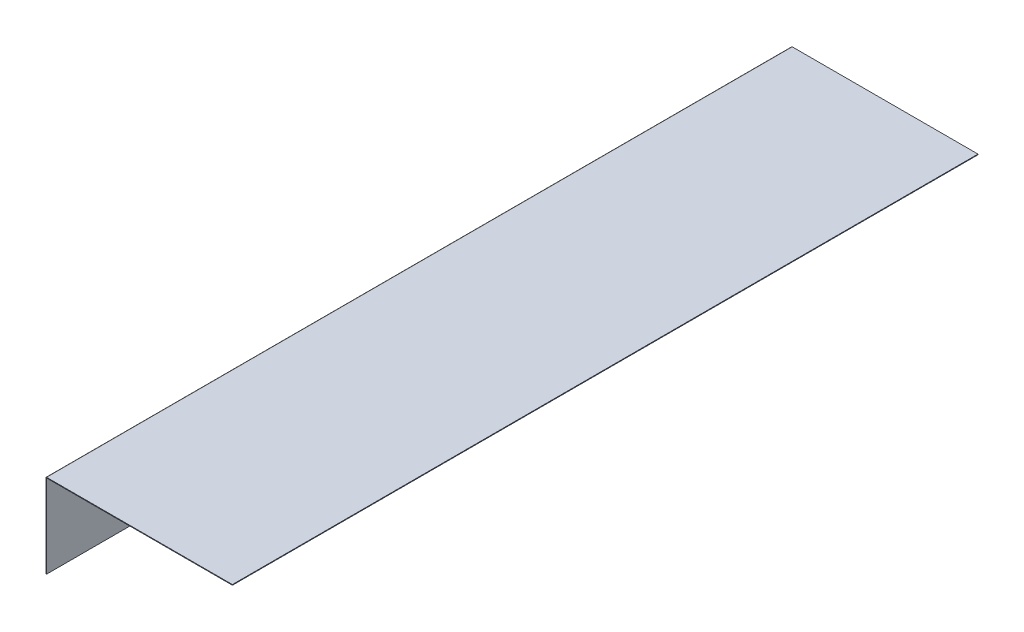
SolidWorks part; units mm, degrees
ref_plane "Front Plane" through (0, 0, 0) normal (0, 0, 1) x (1, 0, 0)
ref_plane "Top Plane" through (0, 0, 0) normal (0, 1, 0) x (1, 0, 0)
ref_plane "Right Plane" through (0, 0, 0) normal (1, 0, 0) x (0, 0, -1)
sketch "Sketch1" plane through (0, 0, 0) normal (0, 0, 1) x (1, 0, 0)
  line L0 (0, 0) -> (0, 135)
  line L1 (0, 135) -> (300, 135)
  line L2 (300, 135) -> (300, 134)
  line L3 (300, 134) -> (1, 134)
  line L4 (1, 134) -> (1, 0)
  line L5 (1, 0) -> (0, 0)
  dimension "D1" = 1
  dimension "D2" = 1
  dimension "D3" = 300
  dimension "D4" = 135
extrude "Boss-Extrude1" add sketch "Sketch1" along normal blind 1200
fillet "Fillet1" radius 1 2 edges at (0, 135, 600) (1, 134, 600)
